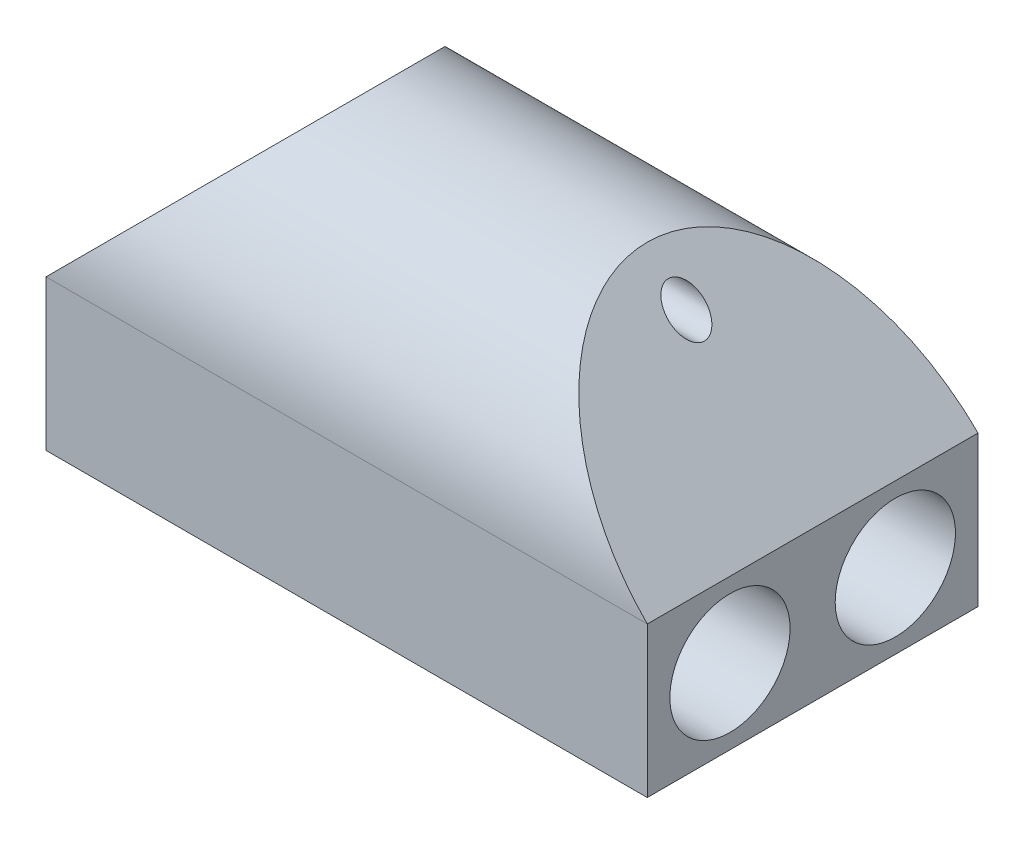
SolidWorks part; units mm, degrees
ref_plane "Front Plane" through (0, 0, 0) normal (0, 0, 1) x (1, 0, 0)
ref_plane "Top Plane" through (0, 0, 0) normal (0, 1, 0) x (1, 0, 0)
ref_plane "Right Plane" through (0, 0, 0) normal (1, 0, 0) x (0, 0, -1)
sketch "Sketch1" plane through (0, 0, 0) normal (0, 1, 0) x (1, 0, 0)
  line L1 (0, 0) -> (-25.4, 0)
  line L2 (0, 0) -> (0, 13.97)
  line L3 (0, 13.97) -> (-25.4, 13.97)
  line L4 (-25.4, 0) -> (-25.4, 13.97)
  dimension "length" = 25.4
  dimension "width" = 13.97
extrude "depth a" add sketch "Sketch1" along normal blind 6.35
sketch "Sketch4" plane through (0, 0, 0) normal (1, 0, 0) x (0, 0, -1)
  line L3 (0, 6.35) -> (13.97, 6.35) construction
  line L4 (0, 6.35) -> (13.97, 6.35)
  arc A0 (0, 6.35) -> (13.97, 6.35) centre (6.985, 6.35) cw
extrude "round extrude" add sketch "Sketch4" against normal up to surface (25.4 mm away) up to face at (-25.4, 3.175, -6.985)
sketch "Sketch5" plane through (0, 0, 0) normal (0, 0, 1) x (1, 0, 0)
  line L0 (0, 6.35) -> (0, 13.335)
  line L1 (0, 13.335) -> (-6.985, 13.335)
  line L2 (0, 13.335) -> (-25.4, 13.335) construction
  line L3 (-6.985, 13.335) -> (0, 6.35)
  line L4 (-12.7, -3.2288) -> (-12.7, 15.9288) construction
  line L6 (-25.4, 6.35) -> (-25.4, 13.335)
  line L7 (-25.4, 13.335) -> (-18.415, 13.335)
  line L8 (-18.415, 13.335) -> (-25.4, 6.35)
  line L9 (-25.4, 6.35) -> (0, 6.35) construction
  point P10 (-12.7, 6.35)
  point P16 (-12.7, 6.35)
  dimension "D1" = 45
extrude "angle cut" cut sketch "Sketch5" against normal through all
sketch "string hole " plane through (0, 0, 0) normal (1, 0, 0) x (0, 0, -1)
  line L0 (6.985, 6.35) -> (6.985, 13.335) construction
  line L1 (13.97, 6.35) -> (0, 6.35) construction
  circle A0 centre (6.985, 11.684) radius 0.762
  arc A1 (13.97, 6.35) -> (0, 6.35) centre (6.985, 6.35) ccw construction
  dimension "D1" = 1.524
  dimension "D2" = 5.334
extrude "string hole cut" cut sketch "string hole " against normal through all
sketch "elastic holes" plane through (0, 0, 0) normal (1, 0, 0) x (0, 0, -1)
  line L1 (13.97, 6.35) -> (0, 6.35) construction
  line L2 (0, 0) -> (13.97, 0) construction
  line L3 (6.985, 0) -> (6.985, 6.35) construction
  line L5 (6.985, 3.175) -> (0, 3.175) construction
  line L7 (0, 6.35) -> (0, 0) construction
  circle A0 centre (3.4925, 3.175) radius 2.54
  circle A1 centre (10.4775, 3.175) radius 2.54
  point P5 (6.985, 6.35)
  point P8 (3.4925, 3.175)
  point P13 (6.985, 3.175)
  point P17 (6.985, 0)
  point P20 (0, 3.175)
  dimension "D1" = 5.08
extrude "elastic hole cut" cut sketch "elastic holes" against normal through all
